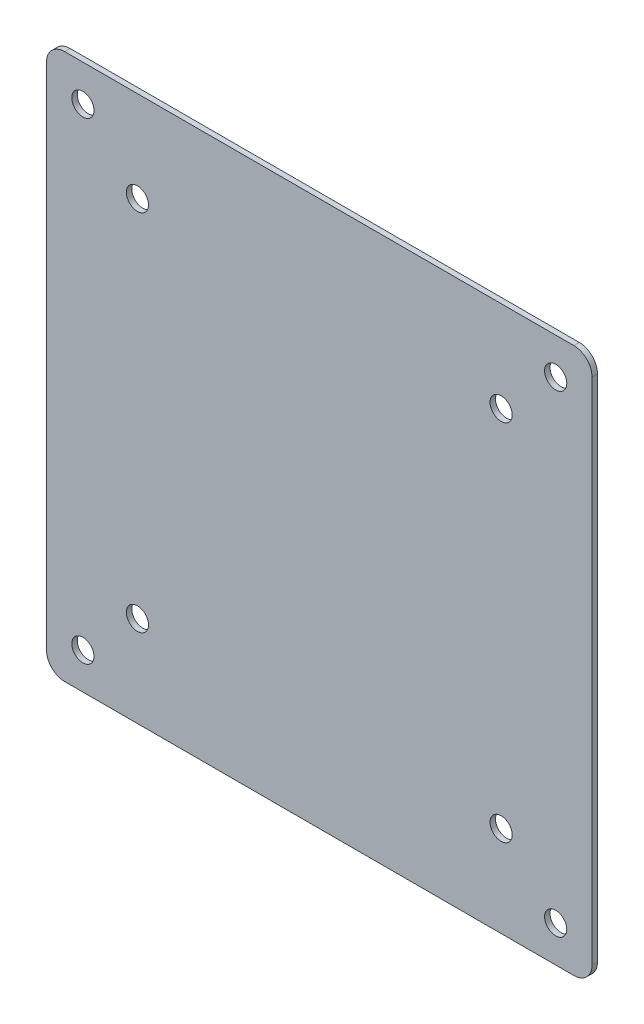
SolidWorks part; units mm, degrees
ref_plane "Front Plane" through (0, 0, 0) normal (0, 0, 1) x (1, 0, 0)
ref_plane "Top Plane" through (0, 0, 0) normal (0, 1, 0) x (1, 0, 0)
ref_plane "Right Plane" through (0, 0, 0) normal (1, 0, 0) x (0, 0, -1)
sketch "Sketch1" plane through (0, 0, 0) normal (0, 0, 1) x (1, 0, 0)
  line L1 (-150, 150) -> (150, 150)
  line L2 (-150, 150) -> (-150, -150)
  line L3 (-150, -150) -> (150, -150)
  line L4 (150, 150) -> (150, -150)
  line L5 (-150, 150) -> (150, -150) construction
  line L6 (-150, -150) -> (150, 150) construction
  point P0 (0, 0)
  dimension "D1" = 300
  dimension "D2" = 300
extrude "Boss-Extrude1" add sketch "Sketch1" along normal blind 3
sketch "Sketch3" plane through (0, 0, 3) normal (0, 0, 1) x (1, 0, 0)
  line L0 (-150, -150) -> (150, 150)
  line L1 (-150, 150) -> (150, -150)
hole_wizard "Ø12.2 (12.2) Diameter Hole1" positions "Sketch4" profile "Sketch5" hole size "Ø12.2" standard "ISO"
sketch "Sketch4" plane through (0, 0, 3) normal (0, 0, 1) x (1, 0, 0)
  line L0 (-150, -150) -> (150, 150) construction
  line L1 (-150, 150) -> (150, -150) construction
  point P0 (-130, -130)
  point P5 (-100, -100)
  point P7 (130, -130)
  point P11 (100, -100)
  point P15 (130, 130)
  point P17 (-100, 100)
  point P19 (-130, 130)
  point P21 (100, 100)
  dimension "D1" = 130
  dimension "D2" = 100
  dimension "D3" = 130
  dimension "D4" = 100
  dimension "D5" = 100
  dimension "D6" = 130
  dimension "D7" = 100
  dimension "D8" = 130
sketch "Sketch5" plane through (-130, -130, 3) normal (1, 0, 0) x (0, -1, 0)
  line L0 (0, 0) -> (0, 26.6652)
  line L1 (0, 26.6652) -> (6.1, 23)
  line L2 (6.1, 23) -> (6.1, 0)
  line L5 (6.1, 0) -> (0, 0)
  line L10 (0, 26.6652) -> (-6.1, 23) construction
  line L11 (0, -6.35) -> (0, 107.95) construction
  dimension "Hole Dia." = 12.2
  dimension "Hole Depth" = 23
  dimension "Drill Angle" = 118
fillet "Fillet1" radius 10 4 edges at (150, 150, 1.5) (150, -150, 1.5) (-150, 150, 1.5) (-150, -150, 1.5)
